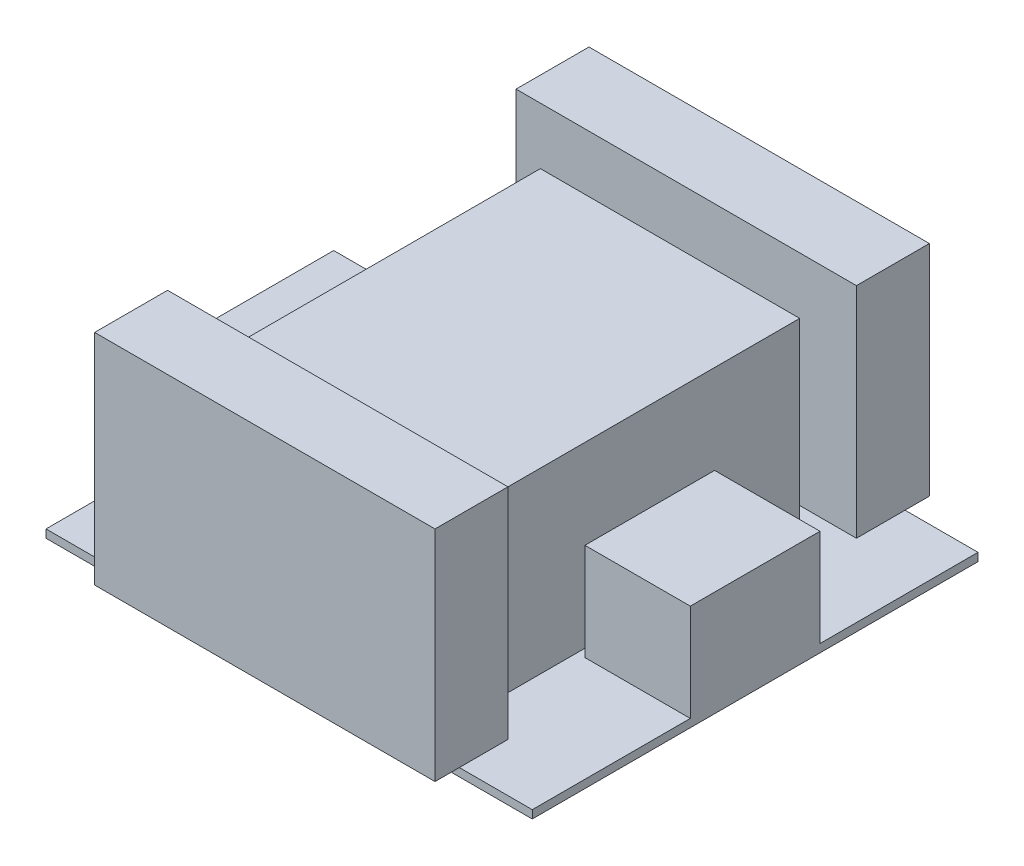
SolidWorks part; units mm, degrees
material "E-Glass Fiber"
ref_plane "Front Plane" through (0, 0, 0) normal (0, 0, 1) x (1, 0, 0)
ref_plane "Top Plane" through (0, 0, 0) normal (0, 1, 0) x (1, 0, 0)
ref_plane "Right Plane" through (0, 0, 0) normal (1, 0, 0) x (0, 0, -1)
sketch "Sketch1" plane through (0, 0, 0) normal (0, 1, 0) x (1, 0, 0)
  line L1 (-30, -27.5) -> (30, -27.5)
  line L2 (-30, -27.5) -> (-30, 27.5)
  line L3 (-30, 27.5) -> (30, 27.5)
  line L4 (30, -27.5) -> (30, 27.5)
  line L5 (-30, -27.5) -> (30, 27.5) construction
  line L6 (-30, 27.5) -> (30, -27.5) construction
  point P0 (0, 0)
  dimension "D1" = 60
  dimension "D2" = 55
extrude "Boss-Extrude1" add sketch "Sketch1" along normal blind 1
sketch "Sketch2" plane through (0, 1, 0) normal (0, 1, 0) x (1, 0, 0)
  line L0 (0, 0) -> (43.7116, 0) construction
  line L1 (-21, 30.5) -> (21, 30.5)
  line L2 (-21, 30.5) -> (-21, 21.5)
  line L3 (-21, 21.5) -> (21, 21.5)
  line L4 (21, 30.5) -> (21, 21.5)
  line L5 (-21, -21.5) -> (21, -21.5)
  line L6 (21, -30.5) -> (21, -21.5)
  line L7 (-21, -30.5) -> (21, -30.5)
  line L8 (-21, -30.5) -> (-21, -21.5)
  line L9 (-30, 27.5) -> (-30, -27.5) construction
  line L10 (30, -27.5) -> (30, 27.5) construction
  line L11 (30, 27.5) -> (-30, 27.5) construction
  dimension "D1" = 9
  dimension "D2" = 9
  dimension "D3" = 9
  dimension "D4" = 3
extrude "Boss-Extrude2" add sketch "Sketch2" along normal blind 27
sketch "Sketch3" plane through (0, 1, 0) normal (0, 1, 0) x (1, 0, 0)
  line L0 (-30, 27.5) -> (-30, -27.5) construction
  line L1 (-30, 8) -> (-17, 8)
  line L2 (-30, 8) -> (-30, -8)
  line L3 (-30, -8) -> (-17, -8)
  line L4 (-17, 8) -> (-17, -8)
  line L5 (0, 0) -> (0, 19.9078) construction
  line L6 (30, -8) -> (17, -8)
  line L7 (17, 8) -> (17, -8)
  line L8 (30, 8) -> (17, 8)
  line L9 (30, 8) -> (30, -8)
  point P13 (-30, 0)
  dimension "D1" = 16
  dimension "D2" = 13
extrude "Boss-Extrude3" add sketch "Sketch3" along normal blind 12
sketch "Sketch4" plane through (0, 1, 0) normal (0, 1, 0) x (1, 0, 0)
  line L0 (-21, 21.5) -> (21, 21.5) construction
  line L1 (-16, -19.5) -> (16, -19.5)
  line L2 (-16, -19.5) -> (-16, 19.5)
  line L3 (-16, 19.5) -> (16, 19.5)
  line L4 (16, -19.5) -> (16, 19.5)
  line L5 (-16, -19.5) -> (16, 19.5) construction
  line L6 (-16, 19.5) -> (16, -19.5) construction
  line L7 (-17, -8) -> (-17, 8) construction
  point P0 (0, 0)
  dimension "D1" = 2
  dimension "D2" = 1
extrude "Boss-Extrude4" add sketch "Sketch4" along normal offset from surface (22 mm away) 5 up to face at (0, 28, -26)
